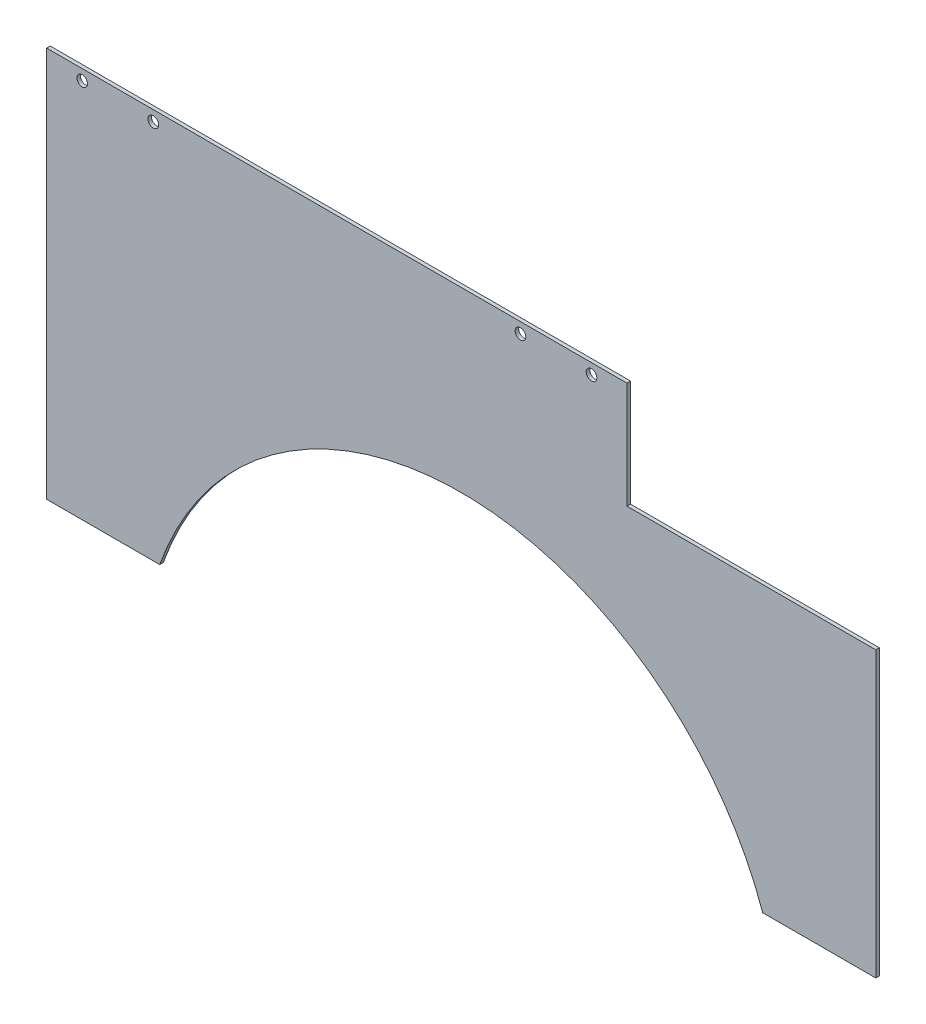
SolidWorks part; units mm, degrees
ref_plane "前视基准面" through (0, 0, 0) normal (0, 0, 1) x (1, 0, 0)
ref_plane "上视基准面" through (0, 0, 0) normal (0, 1, 0) x (1, 0, 0)
ref_plane "右视基准面" through (0, 0, 0) normal (1, 0, 0) x (0, 0, -1)
sketch "草图1" plane through (0, 0, 0) normal (0, 0, 1) x (1, 0, 0)
  line L0 (116.6726, 0) -> (116.6726, -116.6726) construction
  line L1 (0, 0) -> (233.3452, 0)
  line L2 (0, 0) -> (0, 110)
  line L3 (0, 110) -> (233.3452, 110)
  line L4 (233.3452, 0) -> (233.3452, 110)
  line L5 (116.6726, -116.6726) -> (0, 0) construction
  line L6 (116.6726, -116.6726) -> (233.3452, 0) construction
  line L7 (116.6726, 110) -> (116.6726, 0) construction
  line L8 (10, 110) -> (10, 107) construction
  line L9 (10, 107) -> (30, 107) construction
  circle A0 centre (10, 107) radius 1.5
  circle A1 centre (30, 107) radius 1.5
  circle A2 centre (203.3452, 107) radius 1.5
  circle A3 centre (223.3452, 107) radius 1.5
  dimension "D3" = 3
  dimension "D1" = 165
  dimension "D2" = 110
  dimension "D4" = 3
  dimension "D5" = 10
  dimension "D6" = 20
extrude "凸台-拉伸1" add sketch "草图1" along normal blind 1
sketch "草图2" plane through (0, 0, 1) normal (0, 0, 1) x (1, 0, 0)
  line L0 (233.3452, 110) -> (0, 110) construction
  line L1 (163.3452, 110) -> (233.3452, 110)
  line L2 (163.3452, 110) -> (163.3452, 80)
  line L3 (163.3452, 80) -> (233.3452, 80)
  line L4 (233.3452, 110) -> (233.3452, 80)
  line L5 (233.3452, 0) -> (233.3452, 110) construction
  dimension "D1" = 30
  dimension "D2" = 70
extrude "切除-拉伸1" cut sketch "草图2" against normal through all
sketch "草图3" plane through (0, 0, 1) normal (0, 0, 1) x (1, 0, 0)
  line L0 (81.6726, 110) -> (81.6726, 0) construction
  line L1 (163.3452, 110) -> (0, 110) construction
  line L2 (0, 0) -> (233.3452, 0) construction
  circle A0 centre (10, 107) radius 1.5 construction
  circle A1 centre (30, 107) radius 1.5 construction
  circle A2 centre (10, 107) radius 1.5
  circle A3 centre (30, 107) radius 1.5
  circle A4 centre (133.3452, 107) radius 1.5
  circle A5 centre (153.3452, 107) radius 1.5
extrude "切除-拉伸2" cut sketch "草图3" against normal through all
sketch "草图4" plane through (0, 0, 1) normal (0, 0, 1) x (1, 0, 0)
  line L0 (116.6726, 0) -> (116.6726, -30) construction
  line L1 (0, 0) -> (233.3452, 0) construction
  line L2 (116.6726, 60) -> (116.6726, 110) construction
  line L3 (163.3452, 110) -> (0, 110) construction
  circle A0 centre (116.6726, -30) radius 90
  dimension "D1" = 180
  dimension "D2" = 50
extrude "切除-拉伸3" cut sketch "草图4" against normal through all
